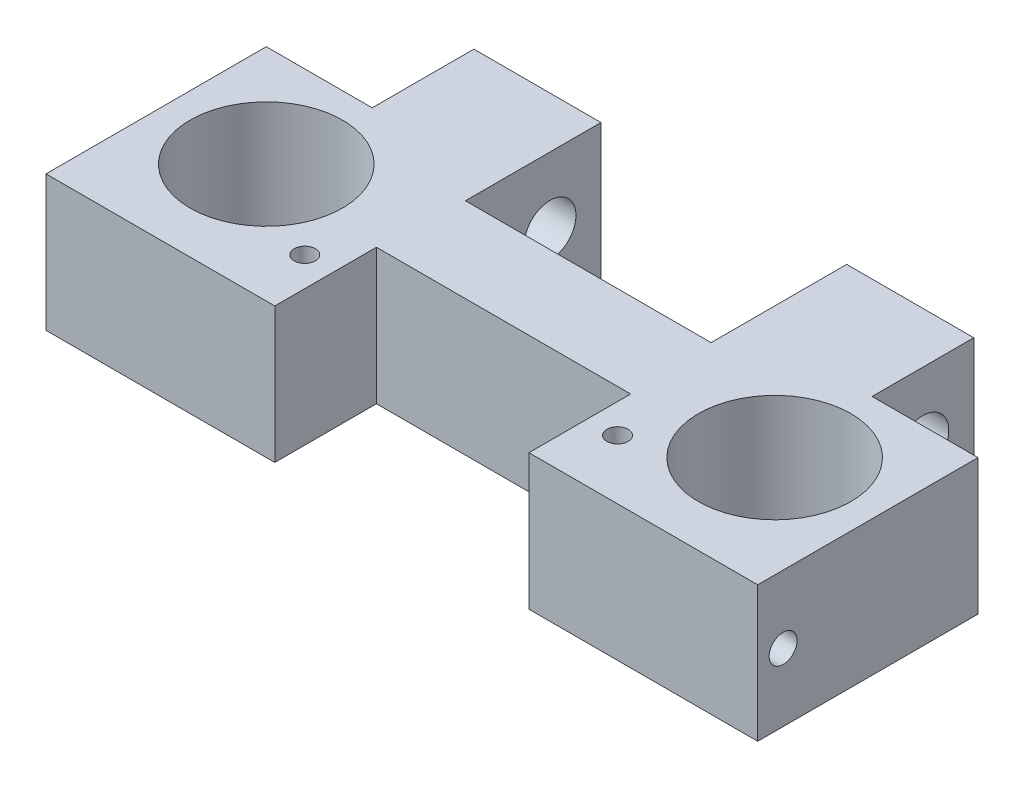
SolidWorks part; units mm, degrees
material "1060 合金"
ref_plane "前视基准面" through (0, 0, 0) normal (0, 0, 1) x (1, 0, 0)
ref_plane "上视基准面" through (0, 0, 0) normal (0, 1, 0) x (1, 0, 0)
ref_plane "右视基准面" through (0, 0, 0) normal (1, 0, 0) x (0, 0, -1)
sketch "草图1" plane through (0, 0, 0) normal (0, 1, 0) x (1, 0, 0)
  line L0 (0, 0) -> (-41.4451, 0) construction
  line L1 (-42, -13) -> (42, -13)
  line L2 (-42, -13) -> (-42, 13)
  line L3 (-42, 13) -> (-29.5, 13)
  line L4 (42, -13) -> (42, 13)
  line L5 (-42, -13) -> (42, 13) construction
  line L6 (-42, 13) -> (42, -13) construction
  line L7 (0, 0) -> (0, 32.1264) construction
  line L8 (-29.5, 13) -> (-29.5, 25)
  line L9 (-29.5, 25) -> (-14.5, 25)
  line L10 (-14.5, 25) -> (-14.5, 9)
  line L11 (14.5, 25) -> (14.5, 9)
  line L12 (29.5, 25) -> (14.5, 25)
  line L13 (29.5, 13) -> (29.5, 25)
  line L14 (-14.5, 9) -> (14.5, 9)
  line L15 (29.5, 13) -> (42, 13)
  circle A0 centre (-30, 1) radius 9
  circle A1 centre (30, 1) radius 9
  point P0 (0, 0)
  dimension "D1" = 60
  dimension "D2" = 18
  dimension "D6" = 12
  dimension "D3" = 29
  dimension "D4" = 15
  dimension "D5" = 12
  dimension "D7" = 22
  dimension "D8" = 12
  dimension "D9" = 5
extrude "凸台-拉伸1" add sketch "草图1" along normal mid plane 16
sketch "草图7" plane through (-29.5, 0, 0) normal (-1, 0, 0) x (0, 0, 1)
  circle A0 centre (-19, 0) radius 3.05
  dimension "D1" = 6.1
  dimension "D2" = 19
extrude "切除-拉伸1" cut sketch "草图7" against normal through all
sketch "草图10" plane through (0, -8, 0) normal (0, -1, 0) x (1, 0, 0)
  line L0 (-42, 13) -> (42, 13) construction
  line L1 (-15, 1) -> (15, 1)
  line L2 (-15, 1) -> (-15, 13)
  line L3 (-15, 13) -> (15, 13)
  line L4 (15, 1) -> (15, 13)
  line L5 (-15, 1) -> (15, 13) construction
  line L6 (-15, 13) -> (15, 1) construction
  point P0 (0, 7)
  dimension "D1" = 30
  dimension "D2" = 12
extrude "切除-拉伸2" cut sketch "草图10" against normal up to next
hole_wizard "M4 螺纹孔1" positions "草图9" profile "草图8" tap size "M4" standard "GB"
sketch "草图9" plane through (42, 0, 0) normal (-1, 0, 0) x (0, 0, 1)
  point P0 (10, 0)
  dimension "D1" = 10
cosmetic thread "孔螺蚊线1" parameters "D1"=9.5, "D2"=4
sketch "草图8" plane through (42, 0, 10) normal (0, 1, 0) x (0, 0, -1)
  line L0 (0, 0) -> (0, 10.4914)
  line L1 (0, 10.4914) -> (1.65, 9.5)
  line L2 (1.65, 9.5) -> (1.65, 0)
  line L5 (1.65, 0) -> (0, 0)
  line L10 (0, 10.4914) -> (-1.65, 9.5) construction
  line L11 (0, -6.35) -> (0, 107.95) construction
  dimension "螺纹孔钻头直径" = 3.3
  dimension "螺纹孔钻头深度" = 9.5
  dimension "导头角度" = 118
chamfer "倒角1" [suppressed] distance 3 angle 45
mirror "镜向1" about plane through (0, 0, 0) normal (1, 0, 0) of "M4 螺纹孔1"
hole_wizard "M3 螺纹孔1" positions "草图12" profile "草图11" tap size "M3" standard "GB"
sketch "草图12" plane through (0, 8, 0) normal (0, 1, 0) x (1, 0, 0)
  line L1 (0, 0) -> (0, -23.7693) construction
  line L3 (-42, -13) -> (-15, -13) construction
  circle A3 centre (-30, 1) radius 9 construction
  point P0 (-18.4566, -6)
  point P9 (18.4566, -6)
  dimension "D1" = 4.5
  dimension "D2" = 7
sketch "草图11" plane through (-18.4566, 8, 6) normal (1, 0, 0) x (0, 0, 1)
  line L0 (0, 0) -> (0, 9.2511)
  line L1 (0, 9.2511) -> (1.25, 8.5)
  line L2 (1.25, 8.5) -> (1.25, 0)
  line L5 (1.25, 0) -> (0, 0)
  line L10 (0, 9.2511) -> (-1.25, 8.5) construction
  line L11 (0, -6.35) -> (0, 107.95) construction
  dimension "螺纹孔钻头直径" = 2.5
  dimension "螺纹孔钻头深度" = 8.5
  dimension "导头角度" = 118
cosmetic thread "孔螺蚊线2" parameters "D1"=6, "D2"=3
cosmetic thread "孔螺蚊线3" parameters "D1"=6, "D2"=3
